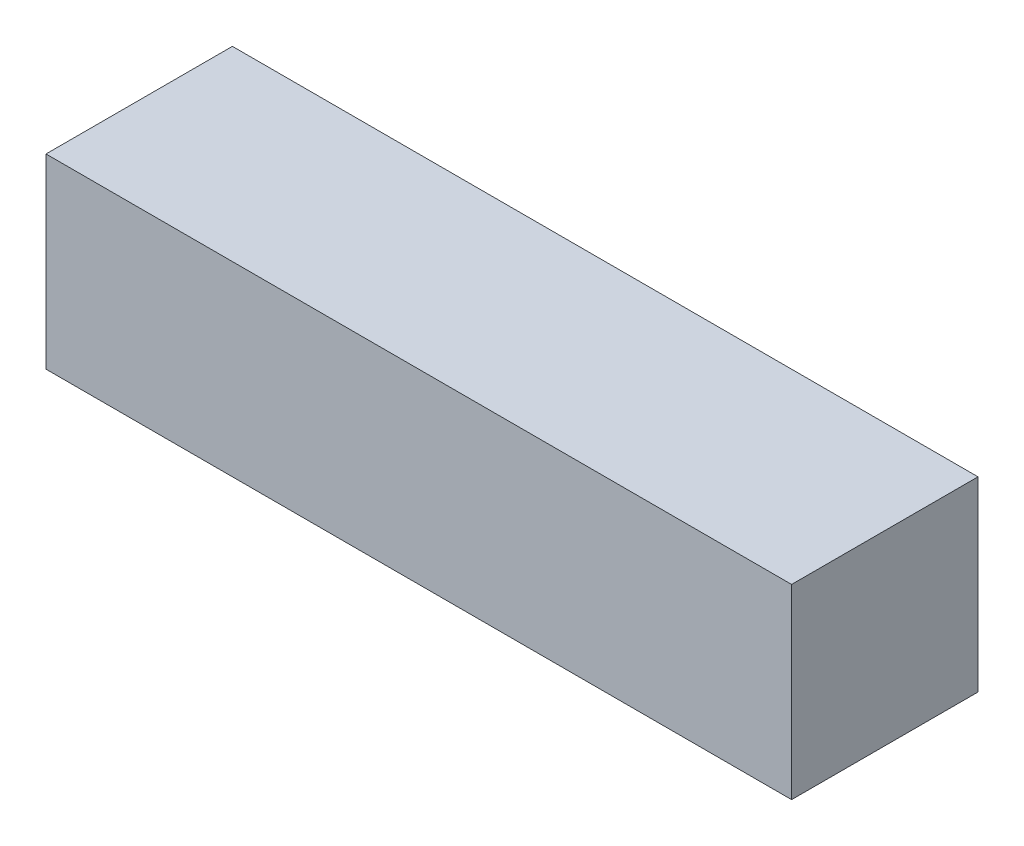
SolidWorks part; units mm, degrees
ref_plane "Front Plane" through (0, 0, 0) normal (0, 0, 1) x (1, 0, 0)
ref_plane "Top Plane" through (0, 0, 0) normal (0, 1, 0) x (1, 0, 0)
ref_plane "Right Plane" through (0, 0, 0) normal (1, 0, 0) x (0, 0, -1)
sketch "Sketch1" plane through (0, 0, 0) normal (1, 0, 0) x (0, 0, -1)
  line L1 (0, 0) -> (2.54, 0)
  line L2 (0, 0) -> (0, 2.54)
  line L3 (0, 2.54) -> (2.54, 2.54)
  line L4 (2.54, 0) -> (2.54, 2.54)
  dimension "D1" = 2.54
  dimension "D2" = 2.54
extrude "Boss-Extrude1" add sketch "Sketch1" along normal blind 10.16
